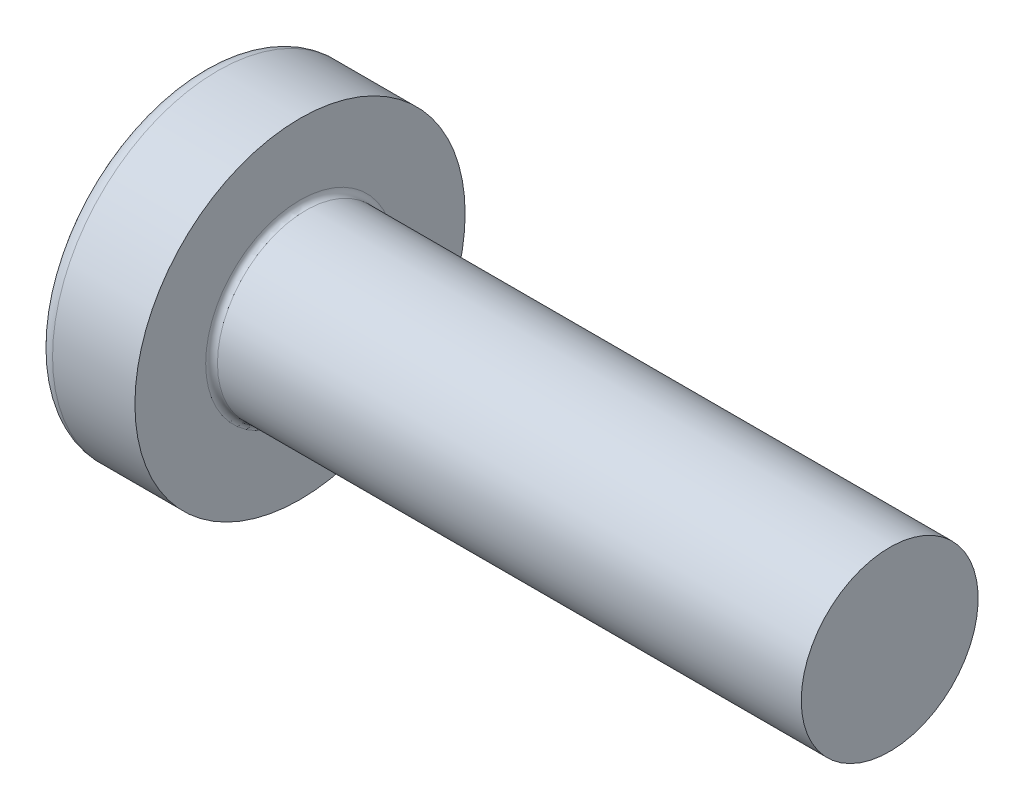
SolidWorks part; units mm, degrees
ref_plane "Plane1" through (0, 0, 0) normal (0, 0, 1) x (1, 0, 0)
ref_plane "Plane2" through (0, 0, 0) normal (0, 1, 0) x (1, 0, 0)
ref_plane "Plane3" through (0, 0, 0) normal (1, 0, 0) x (0, 0, -1)
sketch "BodySke" plane through (0, 0, 0) normal (0, 0, 1) x (1, 0, 0)
  line L0 (2.4, 1.5) -> (2.4, 2.8)
  line L1 (2.65, 6.35) -> (2.65, -3.175) construction
  line L2 (-25.4, 0) -> (127, 0) construction
  line L3 (12.4, 0) -> (0, 0)
  line L4 (2.4, 1.5) -> (12.4, 1.5)
  line L5 (12.4, 1.5) -> (12.4, 0)
  line L6 (1.0035, 2.8) -> (2.4, 2.8)
  line L8 (2.4, 6.35) -> (2.4, -3.175) construction
  arc A0 (0.7754, 2.6744) -> (0, 0) centre (5, 0) ccw
  arc A2 (0.7754, 2.6744) -> (1.0035, 2.8) centre (1.0035, 2.53) cw
  dimension "Head_crown_rad" = 5
  dimension "Head_fillet_rad" = 0.27
  dimension "Length" = 10
  dimension "Head_ht" = 2.4
  dimension "Head_dia" = 5.6
  dimension "Advance" = 0.5
  dimension "Thread_nom" = 10
  dimension "Diameter" = 3
revolve "Base-Revolve" add sketch "BodySke"
cosmetic thread "ThreadCosmetic"
fillet "Fillet1" radius 0.1 1 edges at (2.4, 0, 1.5)
sketch "Sketch3" plane through (0, 0, 0) normal (1, 0, 0) x (0, 0, -1)
  line L0 (0.37, -1.4) -> (-0.37, -1.4)
  line L1 (0.37, -1.4) -> (0.37, 1.4)
  line L2 (-0.37, 1.4) -> (0.37, 1.4)
  line L3 (-0.37, 1.4) -> (-0.37, -1.4)
  dimension "Cross_dia" = 2.8
  dimension "D1" = 1.4
  dimension "Cross_width" = 0.74
  dimension "D2" = 0.37
ref_plane "Plane4" through (1.75, 0, 0) normal (1, 0, 0) x (0, 0, -1)
sketch "Sketch4" plane through (1.75, 0, 0) normal (1, 0, 0) x (0, 0, -1)
  line L0 (0.37, -0.5275) -> (-0.37, -0.5275)
  line L1 (0.37, -0.5275) -> (0.37, 0.5275)
  line L2 (-0.37, 0.5275) -> (0.37, 0.5275)
  line L3 (-0.37, 0.5275) -> (-0.37, -0.5275)
  dimension "D1" = 0.74
  dimension "D2" = 1.055
  dimension "D3" = 0.37
  dimension "D4" = 0.5275
loft "Recess" cut profiles "Sketch3", "Sketch4"
pattern_circular "RecPat" count 2 every 90 about axis through (0, 0, 0) along (1, 0, 0) of "Recess"
sketch "RecCorSke" plane through (0, 0, 0) normal (0, 0, 1) x (1, 0, 0)
  line L0 (-3.175, 0) -> (15.875, 0) construction
  line L1 (-25.4, 0) -> (127, 0) construction
  line L2 (0, 0) -> (0, 0.6784)
  line L3 (0, 0.6784) -> (1.75, 0.556)
  line L4 (1.75, 0.556) -> (1.9307, 0)
  line L5 (1.9307, 0) -> (0, 0)
  dimension "Diameter" = 1.112
  dimension "Depth" = 1.75
  dimension "Draft_angle" = 4
  dimension "Bottom_angle" = 18
revolve "RecessCore" cut sketch "RecCorSke" angle 360 about L0
sketch "ThdSchSke" plane through (0, 0, 0) normal (0, 0, 1) x (1, 0, 0)
  line L0 (3.4, -1.2195) -> (3.2036, -1.5)
  line L1 (3.4, -1.2195) -> (3.5964, -1.5)
  line L2 (3.5964, -1.5) -> (3.5964, -1.875)
  line L3 (-3.175, 0) -> (5.1513, 0) construction
  line L5 (3.5964, -1.875) -> (3.2036, -1.875)
  line L6 (3.2036, -1.875) -> (3.2036, -1.5)
  dimension "Diameter" = 3
  dimension "SideAngle" = 55
  dimension "VeeAngle" = 70
  dimension "Thread_minor" = 2.439
  dimension "Overcut" = 3.75
  dimension "Start" = 3.4
revolve "ThreadSchematic" [suppressed] cut sketch "ThdSchSke" angle 360 about L3
pattern_linear "ThdSchPat" [suppressed]
equation "\"D1@Sketch3\" = \"Cross_dia@Sketch3\" / 2"
equation "\"D2@Sketch3\" = \"Cross_width@Sketch3\" / 2"
equation "\"Depth@RecCorSke\" = \"Cross_depth@Plane4\""
equation "\"D1@Sketch4\" = \"Cross_width@Sketch3\""
equation "\"D2@Sketch4\" = \"Cross_dia@Sketch3\" - 2.0 * \"Cross_depth@Plane4\" * tan(26.5  * 0.017453292)"
equation "\"D3@Sketch4\" = \"D1@Sketch4\" / 2"
equation "\"D4@Sketch4\" = \"D2@Sketch4\" / 2"
equation "\"Thread_length@ThreadCosmetic\" = ((sgn( (\"Length@BodySke\" - \"Advance@BodySke\" * 2.0 ) - \"Thread_nom@BodySke\" )-1)*( (\"Length@BodySke\" - \"Advance@BodySke\" * 2.0 ) - \"Thread_nom@BodySke\" ))/-2+ \"Thread_nom@BodySke\""
equation "\"Thread_minor@ThdSchSke\" = \"Thread_minor@ThreadCosmetic\""
equation "\"Diameter@ThdSchSke\" = \"Diameter@BodySke\""
equation "\"Overcut@ThdSchSke\" = \"Diameter@BodySke\" * 1.25"
equation "\"Start@ThdSchSke\" = \"Head_ht@BodySke\" + \"Length@BodySke\" - \"Thread_length@ThreadCosmetic\"  '---Non-countersunk---"
equation "\"Num_threads@ThdSchPat\" = int( \"Thread_length@ThreadCosmetic\" / \"Advance@BodySke\" + 0.999 )  + 1"
equation "\"Advance@ThdSchPat\" = \"Thread_length@ThreadCosmetic\" /  (\"Num_threads@ThdSchPat\" - 1) 'relax it"
